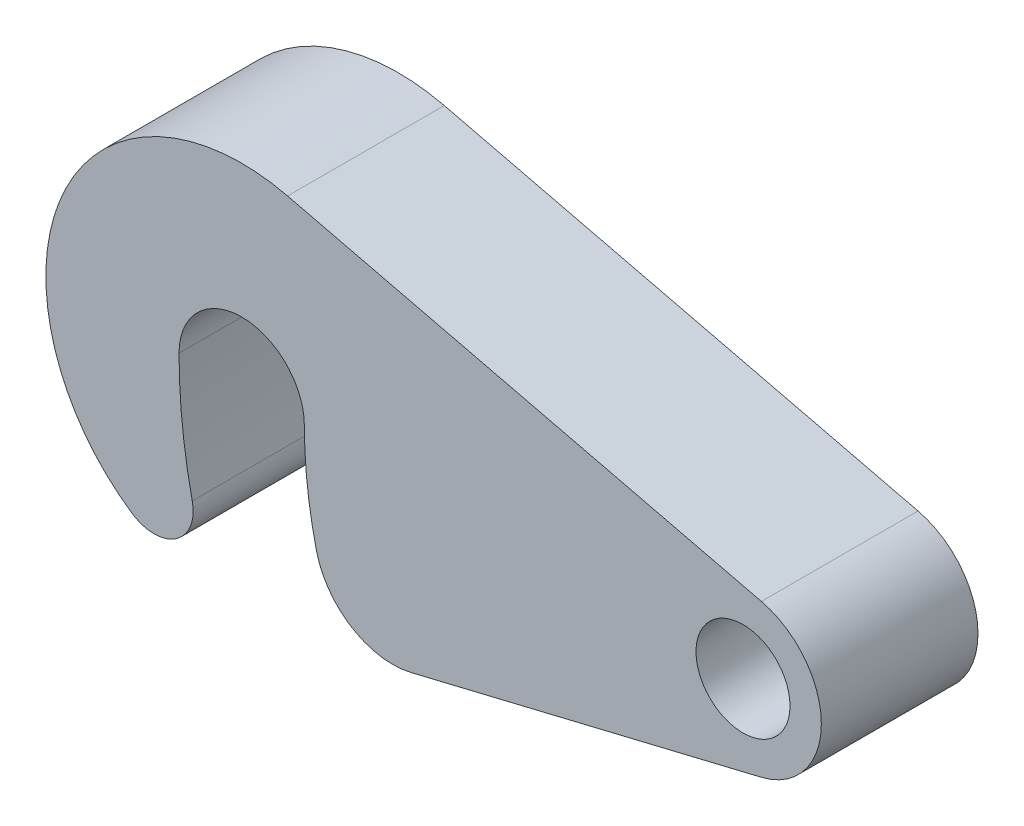
SolidWorks part; units mm, degrees
ref_plane "Front Plane" through (0, 0, 0) normal (0, 0, 1) x (1, 0, 0)
ref_plane "Top Plane" through (0, 0, 0) normal (0, 1, 0) x (1, 0, 0)
ref_plane "Right Plane" through (0, 0, 0) normal (1, 0, 0) x (0, 0, -1)
sketch "Sketch1" plane through (0, 0, 0) normal (0, 0, 1) x (1, 0, 0)
  line L0 (0, 7.2264) -> (0, -33854.6806) construction
  line L1 (0, 0) -> (-33854.6806, 0) construction
  line L2 (5.8594, 24.3037) -> (66.3438, 9.7215)
  line L3 (21.625, -20.5027) -> (66.3438, -9.7215)
  arc A0 (5.8594, 24.3037) -> (-13.9941, -20.7163) centre (0, 0) ccw
  arc A1 (8, 0) -> (-8, 0) centre (0, 0) ccw
  circle A2 centre (64, 0) radius 6
  arc A3 (66.3438, -9.7215) -> (66.3438, 9.7215) centre (64, 0) ccw
  arc A5 (-8, 0) -> (-6.3125, -15.4968) centre (64, 0) ccw
  arc A6 (8, 0) -> (9.5598, -13.125) centre (64, 0) ccw
  arc A7 (-6.3125, -15.4968) -> (-13.9941, -20.7163) centre (-11.1953, -16.573) cw
  arc A8 (9.5598, -13.125) -> (21.625, -20.5027) centre (19.2813, -10.7812) ccw
  dimension "D1" = 50
  dimension "D2" = 16
  dimension "D3" = 20
  dimension "D4" = 12
  dimension "D6" = 5
  dimension "D7" = 10
  dimension "D5" = 64
extrude "Boss-Extrude1" add sketch "Sketch1" along normal mid plane 20
